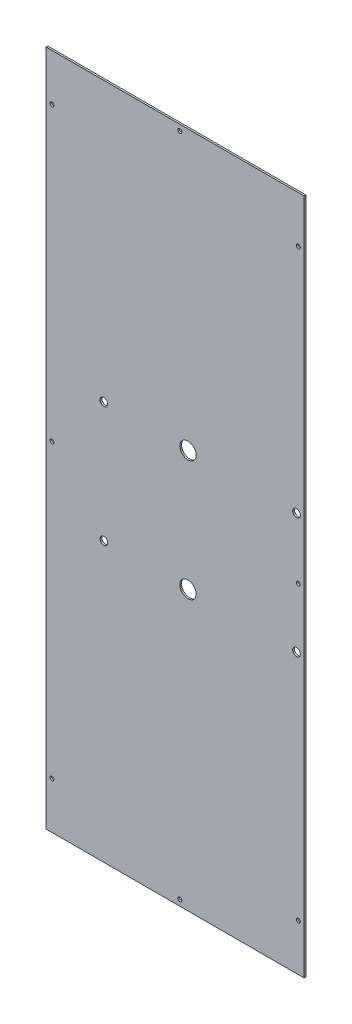
SolidWorks part; units mm, degrees
other "Top Cover Panel 2"
ref_plane "Front Plane" through (0, 0, 0) normal (0, 0, 1) x (1, 0, 0)
ref_plane "Top Plane" through (0, 0, 0) normal (0, 1, 0) x (1, 0, 0)
ref_plane "Right Plane" through (0, 0, 0) normal (1, 0, 0) x (0, 0, -1)
sketch3d "Main Profile Sketch datum points"
  point P0 (0, 0, 111.5)
  point P1 (10, 0, 111.5)
  point P2 (0, 10, 111.5)
ref_plane "Main Profile Sketch plane" through (0, 0, 111.5) normal (0, 0, 1) x (1, 0, 0)
sketch "Main Profile Sketch" plane through (0, 0, 111.5) normal (0, 0, 1) x (1, 0, 0)
  line L0 (-139.5, 290) -> (81.5, 290)
  line L1 (81.5, 290) -> (81.5, -290)
  line L2 (-139.5, -290) -> (81.5, -290)
  line L3 (-139.5, 290) -> (-139.5, -290)
  circle A0 centre (-134.5, -250) radius 1.7
  circle A1 centre (-90, -51.5) radius 3.3
  circle A2 centre (-25, -285) radius 1.7
  circle A3 centre (76.5, -250) radius 1.7
  circle A4 centre (-18, -51.5) radius 7
  circle A5 centre (75, -51.5) radius 3.3
  circle A6 centre (-134.5, 0) radius 1.7
  circle A7 centre (-90, 51.5) radius 3.3
  circle A8 centre (-134.5, 250) radius 1.7
  circle A9 centre (-18, 51.5) radius 7
  circle A10 centre (76.5, 0) radius 1.7
  circle A11 centre (75, 51.5) radius 3.3
  circle A12 centre (-25, 285) radius 1.7
  circle A13 centre (76.5, 250) radius 1.7
extrude "Main Extrusion" add sketch "Main Profile Sketch" against normal blind 1.5 separate body
